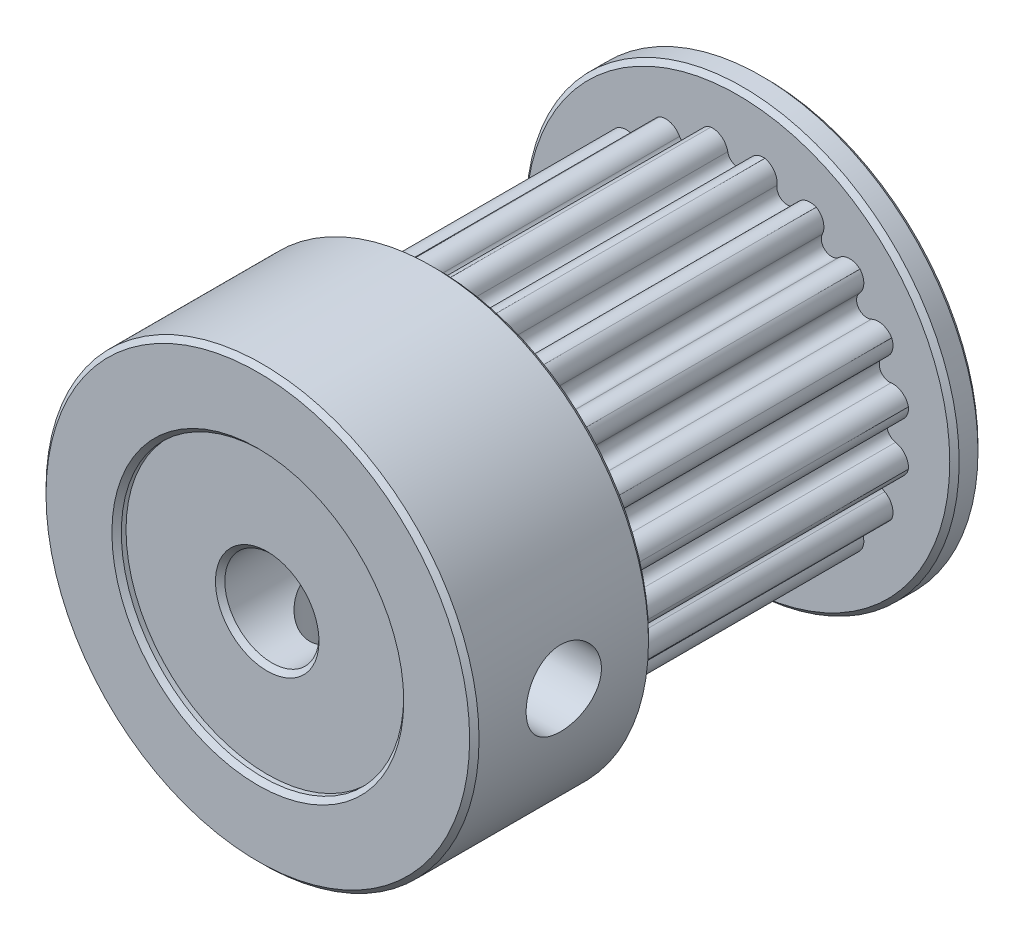
SolidWorks part; units mm, degrees
ref_plane "Plan de face" through (0, 0, 0) normal (0, 0, 1) x (1, 0, 0)
ref_plane "Plan de dessus" through (0, 0, 0) normal (0, 1, 0) x (1, 0, 0)
ref_plane "Plan de droite" through (0, 0, 0) normal (1, 0, 0) x (0, 0, -1)
sketch "Esquisse1" plane through (0, 0, 0) normal (0, 0, 1) x (1, 0, 0)
  circle A0 centre (0, 0) radius 11.5
  circle A1 centre (0, 0) radius 2.5
  dimension "D1" = 23
  dimension "D2" = 5
extrude "Boss.-Extru.1" add sketch "Esquisse1" along normal blind 27
ref_plane "Plan1" through (0, 0, 1.5) normal (0, 0, -1) x (-1, 0, 0)
sketch "Esquisse2" plane through (0, 0, 1.5) normal (0, 0, -1) x (-1, 0, 0)
  circle A0 centre (0, 0) radius 9.17
  circle A1 centre (0, 0) radius 11.5
  dimension "D1" = 18.34
extrude "Enlèv. mat.-Extru.1" cut sketch "Esquisse2" against normal blind 16
sketch "Esquisse3" plane through (0, 0, 17.5) normal (0, 0, -1) x (-1, 0, 0)
  line L0 (-10.9902, 9.17) -> (15.4189, 9.17) construction
  line L1 (0, 0) -> (0, 15.6348) construction
  line L2 (-1.0417, 7.92) -> (1.5586, 7.92) construction
  circle A0 centre (0, 0) radius 9.17 construction
  circle A1 centre (0, 0) radius 9.17 construction
  arc A2 (-1.5, 9.0465) -> (-0.5411, 8.3716) centre (-1.3633, 8.2221) cw
  arc A3 (-0.5411, 8.3716) -> (0.5411, 8.3716) centre (0, 8.47) ccw
  arc A4 (0.5411, 8.3716) -> (1.5, 9.0465) centre (1.3633, 8.2221) cw
  arc A5 (-1.5, 9.0465) -> (1.5, 9.0465) centre (0, 0) cw
  point P17 (0, 0)
  dimension "D2" = 0.55
  dimension "D1" = 1.25
  dimension "D3" = 3
extrude "Enlèv. mat.-Extru.2" cut sketch "Esquisse3" along normal up to surface (16 mm away) up to face at (-9.17, 0, 1.5)
pattern_circular "Répétition circulaire1" count 20 over 360 about axis through (0, 0, 0) along (0, 0, 1) of "Enlèv. mat.-Extru.2"
sketch "Esquisse4" plane through (0, 0, 0) normal (0, 1, 0) x (1, 0, 0)
  line L0 (0, 0) -> (0, -26.9226) construction
  line L3 (-11.5, -17.5) -> (17.9359, -17.5) construction
  line L4 (17.9359, -17.5) -> (17.9359, -27) construction
  line L5 (17.9359, -27) -> (-11.5, -27) construction
  line L6 (-11.5, -27) -> (11.5, -27) construction
  line L7 (0, -22.25) -> (29.4359, -22.25) construction
  circle A0 centre (0, -22.25) radius 2
  dimension "D1" = 4
extrude "Enlèv. mat.-Extru.3" cut sketch "Esquisse4" against normal blind 16
pattern_circular "Répétition circulaire2" count 2 over 90 about axis through (0, 0, 27) along (0, 0, -1) of "Enlèv. mat.-Extru.3"
sketch "Esquisse5" plane through (0, 0, 0) normal (0, 0, -1) x (-1, 0, 0)
  circle A0 centre (0, 0) radius 7.5
  dimension "D1" = 15
extrude "Enlèv. mat.-Extru.4" cut sketch "Esquisse5" against normal blind 0.5
ref_plane "Plan2" through (0, 0, 13.5) normal (0, 0, -1) x (-1, 0, 0)
mirror "Symétrie1" about plane through (0, 0, 13.5) normal (0, 0, -1) of "Enlèv. mat.-Extru.4"
chamfer "Chanfrein1" distance 0.25 angle 45 8 edges at (2.5, 0, 26.5) (-2.5, 0, 0.5) (-7.5, 0, 0) (11.5, 0, 0) (11.5, 0, 27) (-11.5, 0, 17.5) (-11.5, 0, 1.5) (-7.5, 0, 27)
